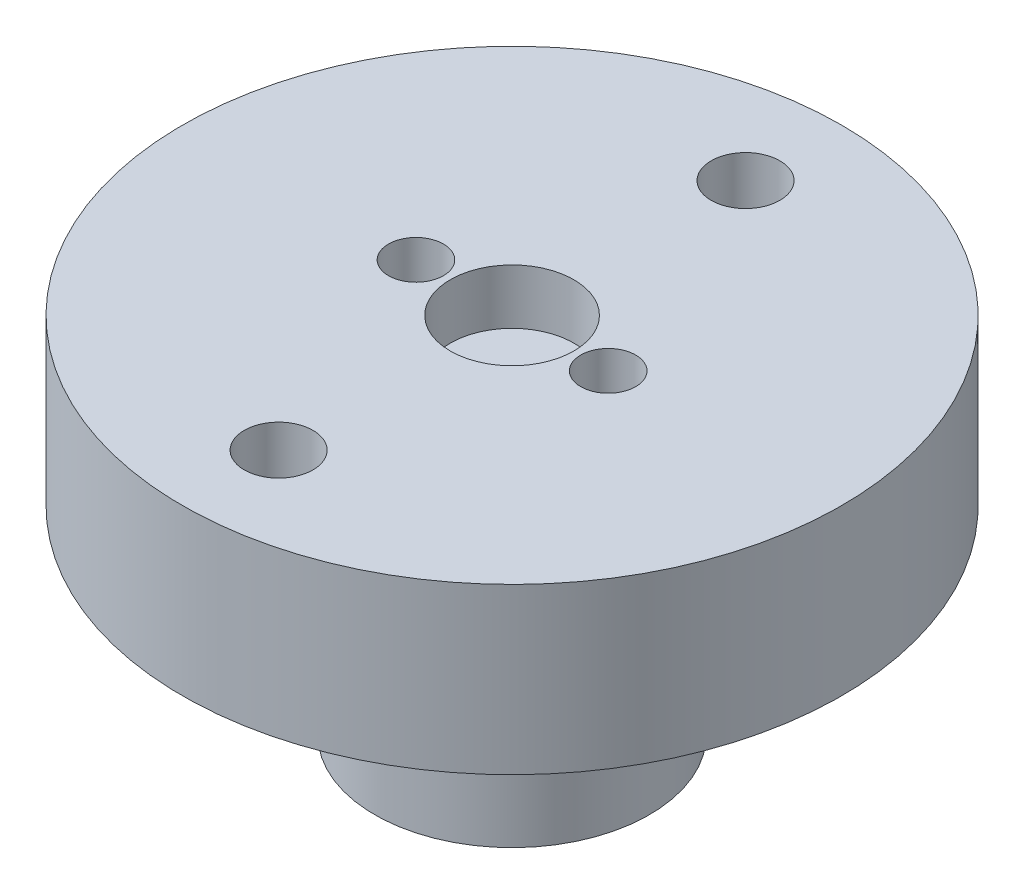
SolidWorks part; units mm, degrees
material "ABS PC"
ref_plane "Front Plane" through (0, 0, 0) normal (0, 0, 1) x (1, 0, 0)
ref_plane "Top Plane" through (0, 0, 0) normal (0, 1, 0) x (1, 0, 0)
ref_plane "Right Plane" through (0, 0, 0) normal (1, 0, 0) x (0, 0, -1)
sketch "Sketch1" plane through (0, 0, 0) normal (0, 0, 1) x (1, 0, 0)
  line L0 (0, 0) -> (0, 15.6368) construction
  line L1 (0, 13.25) -> (0, 0)
  line L2 (0, 13.25) -> (12, 13.25)
  line L3 (6, 5.25) -> (6, 7.25)
  line L4 (6, 5.25) -> (5, 5.25)
  line L5 (5, 5.25) -> (5, 0)
  line L7 (6, 7.25) -> (12, 7.25)
  line L8 (12, 7.25) -> (12, 13.25)
  line L10 (0, 0) -> (5, 0)
  dimension "D1" = 5
  dimension "D2" = 1
  dimension "D3" = 5.25
  dimension "D4" = 2
  dimension "D5" = 12
  dimension "D6" = 6
revolve "Revolve1" add sketch "Sketch1" angle 360 about L0
sketch "Sketch2" plane through (0, 13.25, 0) normal (0, 1, 0) x (1, 0, 0)
  circle A1 centre (3.5, 0) radius 1
  dimension "D3" = 2
  dimension "D4" = 3.5
extrude "Cut-Extrude1" cut sketch "Sketch2" against normal through all
pattern_circular "CirPattern1" count 2 over 360 about axis through (0, 0, 0) along (0, 1, 0) of "Cut-Extrude1"
sketch "Sketch5" plane through (0, 13.25, 0) normal (0, 1, 0) x (1, 0, 0)
  circle A0 centre (0, 8.5) radius 1.25
  circle A1 centre (0, -8.5) radius 1.25
  dimension "D1" = 2.5
  dimension "D2" = 8.5
  dimension "D3" = 8.5
extrude "Cut-Extrude4" cut sketch "Sketch5" against normal blind 10
sketch "Sketch3" plane through (0, 0, 0) normal (0, -1, 0) x (1, 0, 0)
  circle A0 centre (0, 8.5) radius 2.75
  circle A1 centre (0, 8.5) radius 1.25 construction
  circle A2 centre (0, -8.5) radius 2.75
  circle A4 centre (8.5, 0) radius 2.75 [skipped]
  circle A5 centre (-8.5, 0) radius 2.75 [skipped]
  point P12 (0, 0)
  dimension "D1" = 5.5
  dimension "D2" = 4
extrude "Cut-Extrude2" cut sketch "Sketch3" against normal blind 8
sketch "Sketch4" plane through (0, 13.25, 0) normal (0, 1, 0) x (1, 0, 0)
  circle A0 centre (0, 0) radius 2.25
  dimension "D1" = 4.5
extrude "Cut-Extrude3" cut sketch "Sketch4" against normal blind 2
